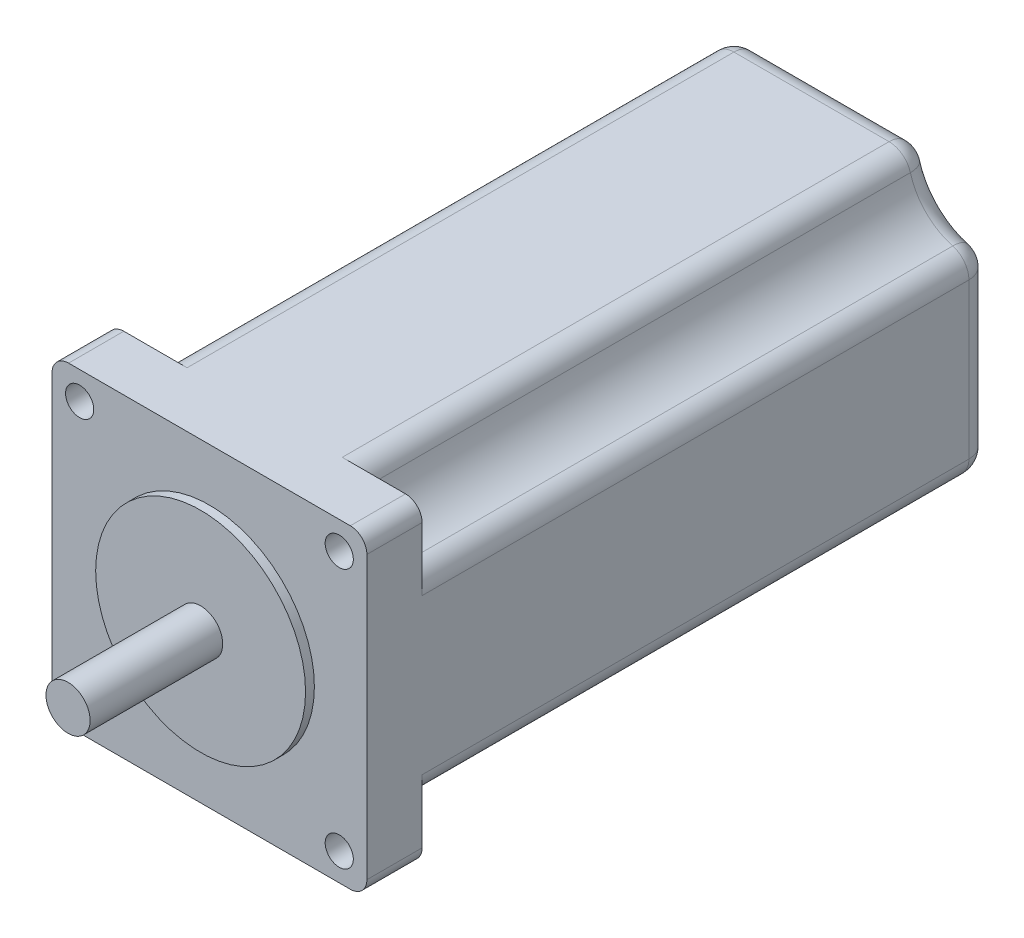
SolidWorks part; units mm, degrees
material "Cast Alloy Steel"
ref_plane "Front Plane" through (0, 0, 0) normal (0, 0, 1) x (1, 0, 0)
ref_plane "Top Plane" through (0, 0, 0) normal (0, 1, 0) x (1, 0, 0)
ref_plane "Right Plane" through (0, 0, 0) normal (1, 0, 0) x (0, 0, -1)
sketch "Sketch1" plane through (0, 0, 0) normal (0, 0, 1) x (1, 0, 0)
  line L0 (-28.5, 28.5) -> (28.5, -28.5) construction
  line L1 (-28.5, 28.5) -> (28.5, 28.5)
  line L2 (-28.5, 28.5) -> (-28.5, -28.5)
  line L3 (-28.5, -28.5) -> (28.5, -28.5)
  line L4 (28.5, 28.5) -> (28.5, -28.5)
  line L5 (28.5, 28.5) -> (-28.5, -28.5) construction
  point P4 (0, 0)
  dimension "D1" = 57
  dimension "D2" = 57
extrude "Boss-Extrude1" add sketch "Sketch1" along normal blind 113
sketch "Sketch2" plane through (0, 0, 0) normal (0, 0, -1) x (-1, 0, 0)
  circle A0 centre (-28.5, 28.5) radius 11
  dimension "D1" = 22
extrude "Cut-Extrude1" cut sketch "Sketch2" against normal offset from surface (103 mm away) 10 up to face at (0, 0, 113)
sketch "Sketch3" plane through (0, 0, 113) normal (0, 0, 1) x (1, 0, 0)
  line L3 (23.5, -23.5) -> (-23.5, -23.5)
  line L4 (23.5, -23.5) -> (23.5, 23.5)
  line L5 (23.5, 23.5) -> (-23.5, 23.5)
  line L6 (-23.5, -23.5) -> (-23.5, 23.5)
  line L7 (23.5, -23.5) -> (-23.5, 23.5) construction
  line L8 (23.5, 23.5) -> (-23.5, -23.5) construction
  circle A1 centre (-23.5, 23.5) radius 2.55
  circle A2 centre (23.5, 23.5) radius 2.55
  circle A3 centre (23.5, -23.5) radius 2.55
  circle A4 centre (-23.5, -23.5) radius 2.55
  point P0 (0, 0)
  point P10 (0, 0)
  dimension "D1" = 47
  dimension "D2" = 47
  dimension "D3" = 5.1
extrude "Cut-Extrude2" cut sketch "Sketch3" against normal through all
fillet "Fillet2" radius 3 1 edges at (28.5, 28.5, 108)
sketch "Sketch4" plane through (0, 0, 113) normal (0, 0, 1) x (1, 0, 0)
  circle A0 centre (0, 0) radius 19
  dimension "D1" = 38
extrude "Boss-Extrude2" add sketch "Sketch4" along normal blind 1.6 contours A0
fillet "Fillet4" radius 3 3 edges at (-28.5, 28.5, 56.5) (-28.5, -28.5, 56.5) (28.5, -28.5, 56.5)
sketch "Sketch6" plane through (0, 0, 114.6) normal (0, 0, 1) x (1, 0, 0)
  circle A0 centre (0, 0) radius 4
  dimension "D1" = 8
extrude "Boss-Extrude3" add sketch "Sketch6" along normal blind 24
sketch "Sketch7" plane through (-28.5, 0, 0) normal (-1, 0, 0) x (0, 0, 1)
  circle A0 centre (12.24, 0) radius 6
  dimension "D1" = 12
extrude "Boss-Extrude4" add sketch "Sketch7" along normal blind 2
pattern_circular "CirPattern4" count 4 over 360 about axis through (0, 0, 0) along (0, 0, 1) of "Cut-Extrude1"
fillet "Fillet5" radius 4 8 edges at (-28.5, 17.5, 51.5) (-17.5, 28.5, 51.5) (17.5, 28.5, 51.5) (28.5, 17.5, 51.5) (-28.5, -17.5, 51.5) (-17.5, -28.5, 51.5) (17.5, -28.5, 51.5) (28.5, -17.5, 51.5)
fillet "Fillet6" radius 4 16 edges at (-27.6833, -16.4653, 0) (-20.7218, -20.7218, 0) (-16.4653, -27.6833, 0) (0, -28.5, 0) (16.4653, -27.6833, 0) (20.7218, -20.7218, 0) (27.6833, -16.4653, 0) (28.5, 0, 0) (27.6833, 16.4653, 0) (20.7218, 20.7218, 0) (16.4653, 27.6833, 0) (0, 28.5, 0) (-16.4653, 27.6833, 0) (-20.7218, 20.7218, 0) (-27.6833, 16.4653, 0) (-28.5, 0, 0)
